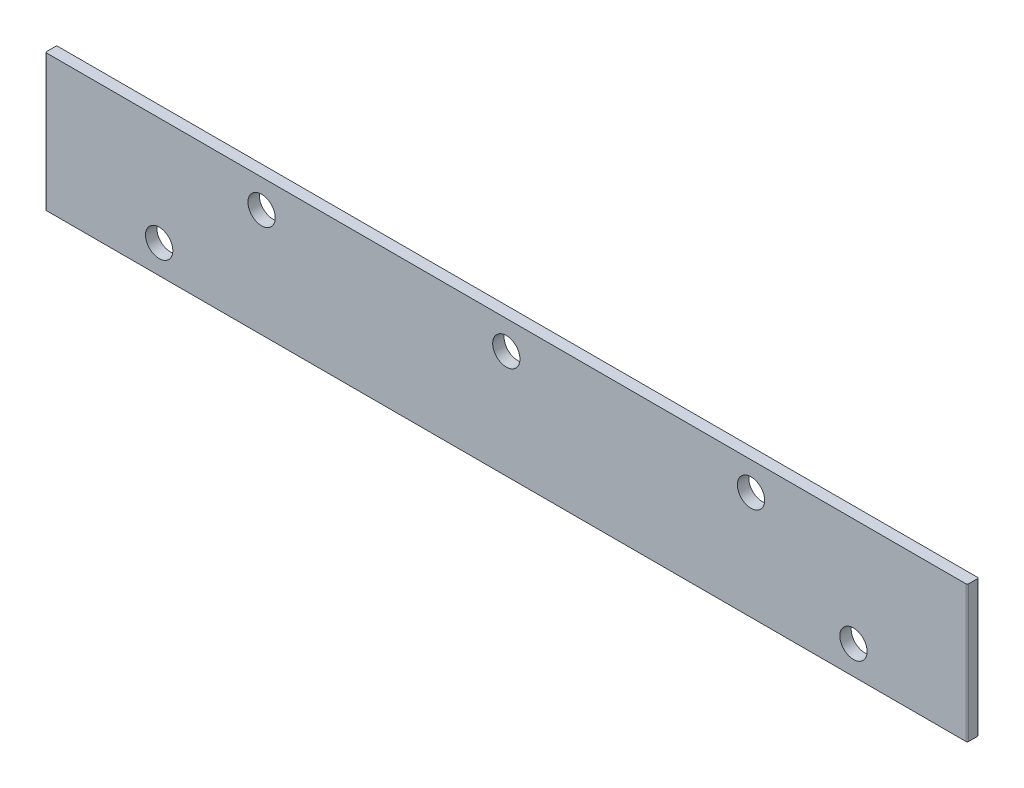
SolidWorks part; units mm, degrees
material "5052-H34"
ref_plane "Frontal" through (0, 0, 0) normal (0, 0, 1) x (1, 0, 0)
ref_plane "Superior" through (0, 0, 0) normal (0, 1, 0) x (1, 0, 0)
ref_plane "Direito" through (0, 0, 0) normal (1, 0, 0) x (0, 0, -1)
sketch "Sketch1" plane through (0, 0, 0) normal (0, 0, 1) x (1, 0, 0)
  line L1 (-40.5, -6) -> (40.5, -6)
  line L2 (-40.5, -6) -> (-40.5, 6)
  line L3 (-40.5, 6) -> (40.5, 6)
  line L4 (40.5, -6) -> (40.5, 6)
  line L5 (-40.5, -6) -> (40.5, 6) construction
  line L6 (-40.5, 6) -> (40.5, -6) construction
  point P0 (0, 0)
  dimension "D1" = 12
  dimension "D2" = 81
extrude "Boss-Extrude1" add sketch "Sketch1" along normal mid plane 1
hole_wizard "M2 Hole1 - AD" positions "Sketch4" profile "Sketch3" hole size "M2" standard "DIN"
sketch "Sketch4" plane through (0, 0, 0.5) normal (0, 0, 1) x (1, 0, 0)
  line L2 (-40.5, 6) -> (-40.5, -6) construction
  line L3 (40.5, -6) -> (40.5, 6) construction
  line L4 (40.5, 6) -> (-40.5, 6) construction
  point P0 (-30.5, -3.5)
  point P2 (30.5, -3.5)
  dimension "D1" = 9.5
  dimension "D3" = 10
  dimension "D4" = 10
sketch "Sketch3" plane through (-30.5, -3.5, 0.5) normal (1, 0, 0) x (0, -1, 0)
  line L0 (0, 0) -> (0, 100.721)
  line L1 (0, 100.721) -> (1.2, 100)
  line L2 (1.2, 100) -> (1.2, 0)
  line L5 (1.2, 0) -> (0, 0)
  line L10 (0, 100.721) -> (-1.2, 100) construction
  line L11 (0, -6.35) -> (0, 107.95) construction
  dimension "Hole Dia." = 2.4
  dimension "Hole Depth" = 100
  dimension "Drill Angle" = 118
hole_wizard "M2 Hole2 - AD" positions "Sketch6" profile "Sketch5" hole size "M2" standard "DIN"
sketch "Sketch6" plane through (0, 0, 0.5) normal (0, 0, 1) x (1, 0, 0)
  line L0 (40.5, 6) -> (-40.5, 6) construction
  line L2 (-40.5, 6) -> (-40.5, -6) construction
  line L3 (40.5, -6) -> (40.5, 6) construction
  point P0 (-21.5, 3.5)
  point P2 (21.5, 3.5)
  dimension "D1" = 2.5
  dimension "D3" = 19
  dimension "D4" = 19
sketch "Sketch5" plane through (-21.5, 3.5, 0.5) normal (1, 0, 0) x (0, -1, 0)
  line L0 (0, 0) -> (0, 100.721)
  line L1 (0, 100.721) -> (1.2, 100)
  line L2 (1.2, 100) -> (1.2, 0)
  line L5 (1.2, 0) -> (0, 0)
  line L10 (0, 100.721) -> (-1.2, 100) construction
  line L11 (0, -6.35) -> (0, 107.95) construction
  dimension "Hole Dia." = 2.4
  dimension "Hole Depth" = 100
  dimension "Drill Angle" = 118
hole_wizard "M2 Hole3 - AE" positions "Sketch8" profile "Sketch7" hole size "M2" standard "DIN"
sketch "Sketch8" plane through (0, 0, 0.5) normal (0, 0, 1) x (1, 0, 0)
  line L1 (40.5, 6) -> (-40.5, 6) construction
  point P0 (0, 3.5)
  dimension "D2" = 2.5
sketch "Sketch7" plane through (0, 3.5, 0.5) normal (1, 0, 0) x (0, -1, 0)
  line L0 (0, 0) -> (0, 200.721)
  line L1 (0, 200.721) -> (1.2, 200)
  line L2 (1.2, 200) -> (1.2, 0)
  line L5 (1.2, 0) -> (0, 0)
  line L10 (0, 200.721) -> (-1.2, 200) construction
  line L11 (0, -6.35) -> (0, 107.95) construction
  dimension "Hole Dia." = 2.4
  dimension "Hole Depth" = 200
  dimension "Drill Angle" = 118
fillet "Fillet1" radius 0.1 4 edges at (40.5, 0, -0.5) (40.5, 0, 0.5) (-40.5, 0, -0.5) (-40.5, 0, 0.5)
